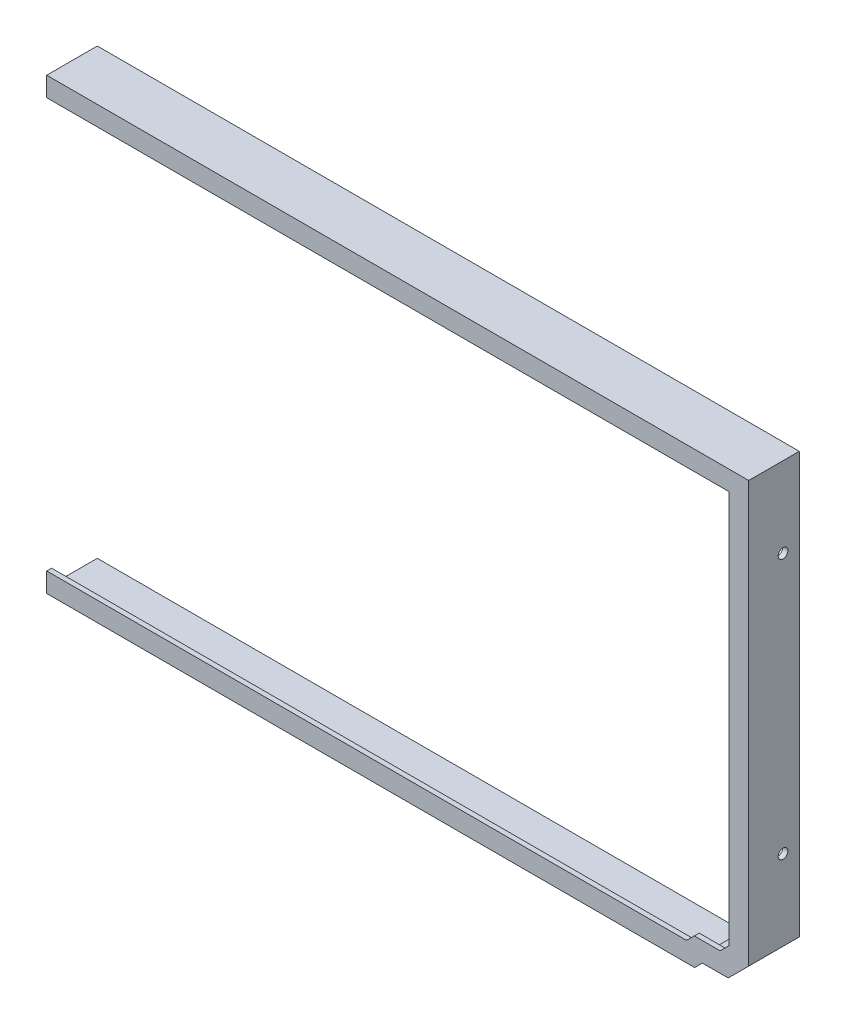
SolidWorks part; units mm, degrees
ref_plane "Přední rovina" through (0, 0, 0) normal (0, 0, 1) x (1, 0, 0)
ref_plane "Horní rovina" through (0, 0, 0) normal (0, 1, 0) x (1, 0, 0)
ref_plane "Pravá rovina" through (0, 0, 0) normal (1, 0, 0) x (0, 0, -1)
sketch "Skica1" plane through (0, 0, 0) normal (0, 0, 1) x (1, 0, 0)
  line L0 (0, 0) -> (428.28, 0) construction
  line L1 (0, 0) -> (0, -126.92) construction
  line L2 (428.28, 0) -> (428.28, -126.92) construction
  line L3 (0, -126.92) -> (5.3104, -132.2304) construction
  line L4 (428.28, -126.92) -> (422.9696, -132.2304) construction
  line L5 (5.3104, -132.2304) -> (13.2504, -132.2304) construction
  line L6 (422.9696, -132.2304) -> (415.0296, -132.2304) construction
  line L7 (13.2504, -132.2304) -> (15.6333, -134.6133) construction
  line L8 (415.0296, -132.2304) -> (412.6467, -134.6133) construction
  line L9 (412.6467, -134.6133) -> (15.6333, -134.6133) construction
  line L10 (-0.1, 0.1) -> (428.38, 0.1)
  line L11 (428.38, 0.1) -> (428.38, -126.9614)
  line L12 (428.38, -126.9614) -> (423.011, -132.3304)
  line L13 (423.011, -132.3304) -> (415.071, -132.3304)
  line L14 (415.071, -132.3304) -> (412.6881, -134.7133)
  line L15 (412.6881, -134.7133) -> (15.5919, -134.7133)
  line L16 (13.209, -132.3304) -> (15.5919, -134.7133)
  line L17 (5.269, -132.3304) -> (13.209, -132.3304)
  line L18 (-0.1, -126.9614) -> (5.269, -132.3304)
  line L19 (-0.1, 0.1) -> (-0.1, -126.9614)
  line L20 (-1.7, 1.7) -> (429.98, 1.7)
  line L21 (429.98, 1.7) -> (429.98, -127.6242)
  line L22 (429.98, -127.6242) -> (423.6738, -133.9304)
  line L23 (423.6738, -133.9304) -> (415.7338, -133.9304)
  line L24 (415.7338, -133.9304) -> (413.3508, -136.3133)
  line L25 (413.3508, -136.3133) -> (14.9292, -136.3133)
  line L26 (12.5462, -133.9304) -> (14.9292, -136.3133)
  line L27 (4.6062, -133.9304) -> (12.5462, -133.9304)
  line L28 (-1.7, -127.6242) -> (4.6062, -133.9304)
  line L29 (-1.7, 1.7) -> (-1.7, -127.6242)
  dimension "D1" = 428.28
  dimension "D2" = 126.92
  dimension "D3" = 126.92
  dimension "D4" = 7.51
  dimension "D5" = 7.51
  dimension "D6" = 135
  dimension "D7" = 135
  dimension "D8" = 7.94
  dimension "D9" = 7.94
  dimension "D10" = 3.37
  dimension "D11" = 3.37
  dimension "D12" = 135
  dimension "D13" = 0.1
  dimension "D14" = 1.6
extrude "Přidat vysunutím1" add sketch "Skica1" against normal blind 14.05
sketch "Skica2" plane through (0, 0, 0) normal (0, 0, 1) x (1, 0, 0)
  line L20 (4.3, -4.3) -> (4.3, -125.1389)
  line L21 (4.3, -125.1389) -> (7.0915, -127.9304)
  line L22 (7.0915, -127.9304) -> (15.0315, -127.9304)
  line L23 (15.0315, -127.9304) -> (17.4144, -130.3133)
  line L24 (17.4144, -130.3133) -> (410.8656, -130.3133)
  line L25 (410.8656, -130.3133) -> (413.2485, -127.9304)
  line L26 (413.2485, -127.9304) -> (421.1885, -127.9304)
  line L27 (421.1885, -127.9304) -> (423.98, -125.1389)
  line L28 (423.98, -125.1389) -> (423.98, -4.3)
  line L29 (423.98, -4.3) -> (4.3, -4.3)
  line L30 (4.3, -4.3) -> (4.3, -125.1389)
  line L31 (4.3, -125.1389) -> (7.0915, -127.9304)
  line L32 (7.0915, -127.9304) -> (15.0315, -127.9304)
  line L33 (15.0315, -127.9304) -> (17.4144, -130.3133)
  line L34 (17.4144, -130.3133) -> (410.8656, -130.3133)
  line L35 (410.8656, -130.3133) -> (413.2485, -127.9304)
  line L36 (413.2485, -127.9304) -> (421.1885, -127.9304)
  line L37 (421.1885, -127.9304) -> (423.98, -125.1389)
  line L38 (423.98, -125.1389) -> (423.98, -4.3)
  line L39 (423.98, -4.3) -> (4.3, -4.3)
  line L50 (-1.7, 1.7) -> (-1.7, -127.6242)
  line L51 (-1.7, -127.6242) -> (4.6062, -133.9304)
  line L52 (4.6062, -133.9304) -> (12.5462, -133.9304)
  line L53 (12.5462, -133.9304) -> (14.9292, -136.3133)
  line L54 (14.9292, -136.3133) -> (413.3508, -136.3133)
  line L55 (413.3508, -136.3133) -> (415.7338, -133.9304)
  line L56 (415.7338, -133.9304) -> (423.6738, -133.9304)
  line L57 (423.6738, -133.9304) -> (429.98, -127.6242)
  line L58 (429.98, -127.6242) -> (429.98, 1.7)
  line L59 (429.98, 1.7) -> (-1.7, 1.7)
  line L60 (-1.7, 1.7) -> (-1.7, -127.6242)
  line L61 (-1.7, -127.6242) -> (4.6062, -133.9304)
  line L62 (4.6062, -133.9304) -> (12.5462, -133.9304)
  line L63 (12.5462, -133.9304) -> (14.9292, -136.3133)
  line L64 (14.9292, -136.3133) -> (413.3508, -136.3133)
  line L65 (413.3508, -136.3133) -> (415.7338, -133.9304)
  line L66 (415.7338, -133.9304) -> (423.6738, -133.9304)
  line L67 (423.6738, -133.9304) -> (429.98, -127.6242)
  line L68 (429.98, -127.6242) -> (429.98, 1.7)
  line L69 (429.98, 1.7) -> (-1.7, 1.7)
  dimension "D1" = 6
  dimension "D2" = 0
extrude "Přidat vysunutím2" add sketch "Skica2" along normal blind 1.5
sketch "Skica3" plane through (0, 1.7, 0) normal (0, 1, 0) x (1, 0, 0)
  line L0 (-1.7, 8.25) -> (43.01, 8.25) construction
  line L1 (-1.7, 14.05) -> (-1.7, -1.5) construction
  line L2 (429.98, -1.5) -> (-1.7, -1.5) construction
  line L3 (45.76, 8.25) -> (40.26, 8.25) construction
  line L4 (45.76, 4.75) -> (40.26, 4.75)
  line L5 (45.76, 11.75) -> (40.26, 11.75)
  arc A0 (45.76, 4.75) -> (45.76, 11.75) centre (45.76, 8.25) ccw
  arc A1 (40.26, 11.75) -> (40.26, 4.75) centre (40.26, 8.25) ccw
  point P6 (40.26, 8.25)
  point P9 (43.01, 8.25)
  dimension "D1" = 9.75
  dimension "D2" = 44.71
  dimension "D3" = 2.75
  dimension "D4" = 7
extrude "Odebrat vysunutím1" cut sketch "Skica3" against normal up to surface (1.6 mm away) up to face at (214.14, 0.1, -7.025)
sketch "Skica4" plane through (-1.7, 0, 0) normal (-1, 0, 0) x (0, 0, 1)
  line L0 (-14.05, -62.9621) -> (1.5, -62.9621) construction
  line L1 (-14.05, 1.7) -> (-14.05, -127.6242) construction
  line L2 (1.5, 1.7) -> (1.5, -127.6242) construction
  circle A0 centre (-9.05, -22.9621) radius 1.5
  circle A1 centre (-9.05, -102.9621) radius 1.5
  dimension "D2" = 3
  dimension "D3" = 3
  dimension "D1" = 40
  dimension "D4" = 5
extrude "Odebrat vysunutím2" cut sketch "Skica4" against normal up to surface (431.68 mm away) up to face at (429.98, -62.9621, -6.275)
sketch "Skica5" plane through (0, 1.7, 0) normal (0, 1, 0) x (1, 0, 0)
  line L0 (429.98, -1.5) -> (-1.7, -1.5) construction
  line L1 (214.14, -1.5) -> (-1.7, -1.5)
  line L2 (214.14, -1.5) -> (214.14, 14.05)
  line L3 (214.14, 14.05) -> (-1.7, 14.05)
  line L4 (-1.7, -1.5) -> (-1.7, 14.05)
  line L5 (-1.7, 14.05) -> (-1.7, -1.5) construction
  line L6 (429.98, 14.05) -> (-1.7, 14.05) construction
extrude "Odebrat vysunutím3" cut sketch "Skica5" against normal through all
